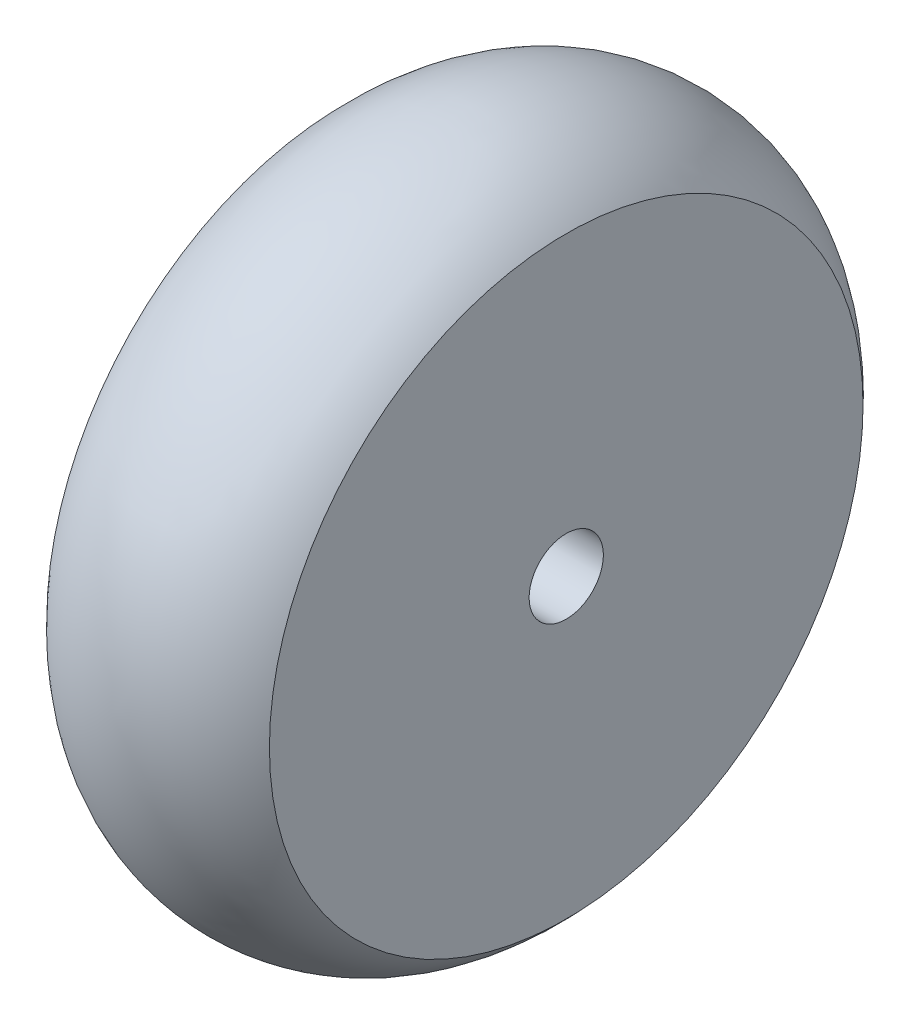
SolidWorks part; units mm, degrees
ref_plane "前基準面" through (0, 0, 0) normal (0, 0, 1) x (1, 0, 0)
ref_plane "上基準面" through (0, 0, 0) normal (0, 1, 0) x (1, 0, 0)
ref_plane "右基準面" through (0, 0, 0) normal (1, 0, 0) x (0, 0, -1)
sketch "草圖1" plane through (0, 0, 0) normal (0, 0, 1) x (1, 0, 0)
  line L0 (-16.6104, 44.0593) -> (-16.6104, 64.0593)
  line L1 (-1.6104, 64.0593) -> (-1.6104, 44.0593)
  line L2 (-1.6104, 44.0593) -> (-16.6104, 44.0593)
  arc A0 (-16.6104, 64.0593) -> (-1.6104, 64.0593) centre (-9.1104, 57.4449) cw
  dimension "D3" = 10
  dimension "D1" = 15
  dimension "D2" = 20
  dimension "D4" = 7.5
revolve "旋轉1" add sketch "草圖1" angle 360 about L2
sketch "草圖2" plane through (-16.6104, 0, 0) normal (-1, 0, 0) x (0, 0, 1)
  circle A0 centre (0, 44.0593) radius 2.5
  circle A1 centre (0, 44.0593) radius 20 construction
  dimension "D1" = 5
extrude "除料-伸長1" cut sketch "草圖2" against normal through all
